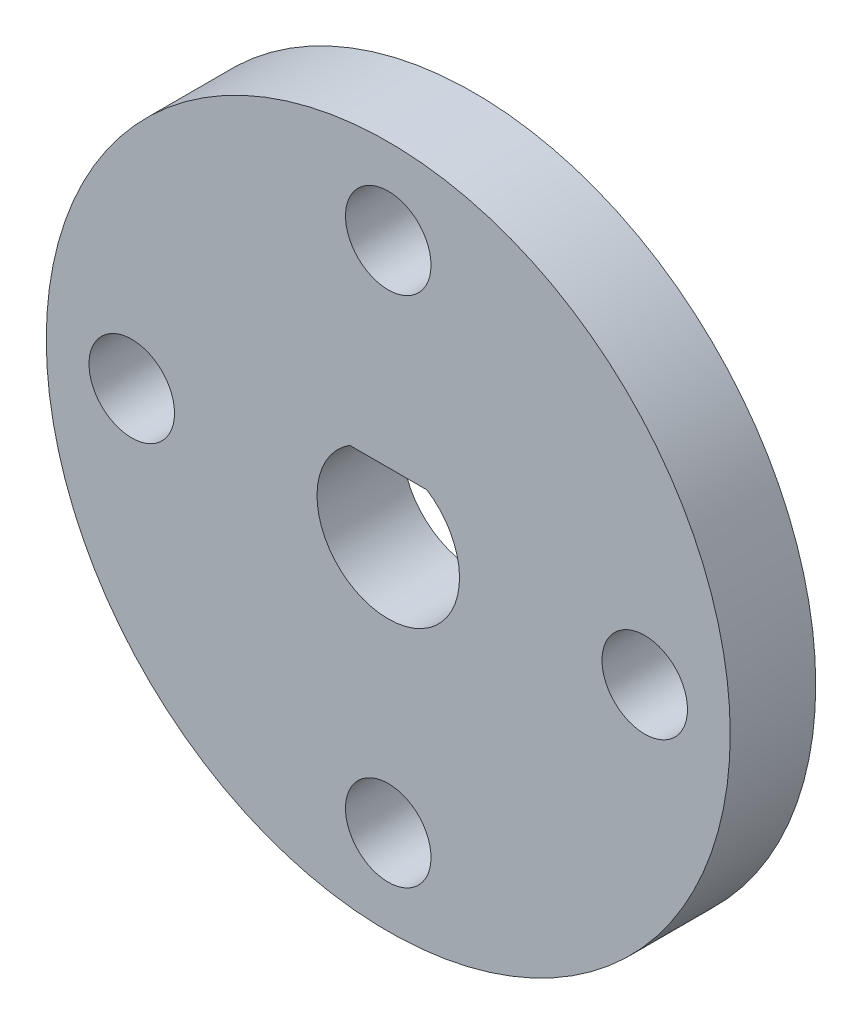
SolidWorks part; units mm, degrees
ref_plane "Alzado" through (0, 0, 0) normal (0, 0, 1) x (1, 0, 0)
ref_plane "Planta" through (0, 0, 0) normal (0, 1, 0) x (1, 0, 0)
ref_plane "Vista lateral" through (0, 0, 0) normal (1, 0, 0) x (0, 0, -1)
sketch "Croquis1" plane through (0, 0, 0) normal (0, 0, 1) x (1, 0, 0)
  line L0 (1.3565, 2.1) -> (-1.3565, 2.1)
  line L1 (0, 12) -> (0, -12) construction
  line L2 (12, 0) -> (-12, 0) construction
  arc A0 (-1.3565, 2.1) -> (1.3565, 2.1) centre (0, 0) ccw
  circle A1 centre (0, 0) radius 12
  circle A2 centre (0, 9) radius 1.5
  circle A3 centre (9, 0) radius 1.5
  circle A4 centre (0, -9) radius 1.5
  circle A5 centre (-9, 0) radius 1.5
  point P20 (0, 0)
  point P22 (0, 0)
  dimension "D1" = 24
  dimension "D2" = 3
  dimension "D3" = 2.5
  dimension "D5" = 3
  dimension "D4" = 2.7129
  dimension "D6" = 4
extrude "Saliente-Extruir1" add sketch "Croquis1" along normal blind 3
